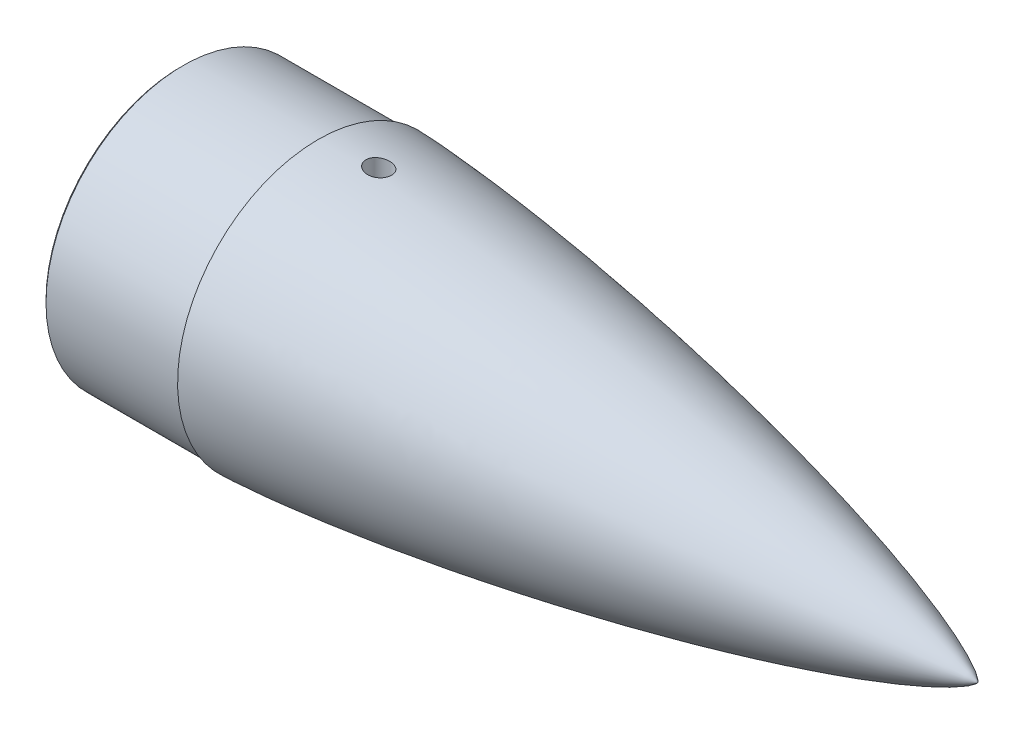
SolidWorks part; units mm, degrees
material "Plain Carbon Steel"
ref_plane "Front Plane" through (0, 0, 0) normal (0, 0, 1) x (1, 0, 0)
ref_plane "Top Plane" through (0, 0, 0) normal (0, 1, 0) x (1, 0, 0)
ref_plane "Right Plane" through (0, 0, 0) normal (1, 0, 0) x (0, 0, -1)
ref_axis "Axis1" through (46.9179, 0, 0) along (-1, 0, 0)
sketch "Sketch10" plane through (0, 0, 0) normal (0, 0, 1) x (1, 0, 0)
  line L1 (-1.0327, 0) -> (486.9547, 0) construction
  line L2 (11.1125, 81.9998) -> (11.1125, 67.4998)
  line L3 (11.1125, 81.9998) -> (-84.6045, 81.9998)
  line L4 (408.9673, 0) -> (368.9673, 0)
  line L5 (-84.6045, 81.9998) -> (-84.6045, 84.9998)
  line L6 (-84.6045, 84.9998) -> (0.3953, 84.9998)
  line L7 (0.3953, 84.9998) -> (0.3953, 86.9998)
  line L8 (11.1125, 67.4998) -> (129.3045, 67.4998)
  spline S0 degree 4 poles (408.9673, 0) (408.9649, 0.0135) (408.958, 0.0399) (408.9365, 0.0905) (408.8922, 0.1741) (408.8263, 0.2756) (408.7217, 0.4158) (408.5611, 0.6051) (408.3056, 0.8724) (407.8697, 1.2753) (407.121, 1.8851) (405.8038, 2.8259) (403.4624, 4.2872) (399.3253, 6.5318) (392.4811, 9.7589) (380.6621, 14.628) (363.6372, 20.7117) (342.2152, 27.4765) (317.4285, 34.4976) (291.8793, 41.1048) (266.2105, 47.229) (240.4455, 52.9334) (214.5989, 58.2554) (188.6809, 63.2176) (165.9462, 67.2533) (146.422, 70.4938) (130.1279, 73.0449) (117.0786, 74.9942) (104.0155, 76.8485) (92.5733, 78.3845) (82.7571, 79.6356) (74.5713, 80.6322) (68.0193, 81.4008) (61.4637, 82.1394) (54.9047, 82.8464) (48.3422, 83.5199) (41.7761, 84.1578) (36.0275, 84.6822) (31.0979, 85.1052) (26.9883, 85.4387) (23.6997, 85.6932) (20.0858, 85.9584) (16.7199, 86.189) (13.6021, 86.387) (10.7327, 86.5546) (8.4366, 86.6787) (6.14, 86.7922) (4.1299, 86.8793) (2.4065, 86.9446) (1.2573, 86.979) (0.6827, 86.9949) (0.3953, 86.9998) knots 0 0 0 0 0 0.00013 0.00026 0.00052 0.0009 0.00128 0.001925 0.002882 0.004418 0.006927 0.011111 0.018279 0.030673 0.051704 0.083102 0.139909 0.202703 0.265496 0.32829 0.391083 0.453877 0.516671 0.579464 0.642258 0.673655 0.705051 0.736448 0.767845 0.799242 0.81494 0.830639 0.846337 0.862036 0.877734 0.893432 0.909131 0.924829 0.932678 0.940527 0.948377 0.956226 0.967169 0.972641 0.978113 0.983585 0.989056 0.994528 0.997264 1 1 1 1 1 construction
  spline S1 degree 4 poles (408.9673, 0) (408.9649, 0.0135) (408.958, 0.0399) (408.9365, 0.0905) (408.8922, 0.1741) (408.8263, 0.2756) (408.7217, 0.4158) (408.5611, 0.6051) (408.3056, 0.8724) (407.8697, 1.2753) (407.121, 1.8851) (405.8038, 2.8259) (403.4624, 4.2872) (399.3253, 6.5318) (392.4811, 9.7589) (380.6621, 14.628) (363.6372, 20.7117) (342.2152, 27.4765) (317.4285, 34.4976) (291.8793, 41.1048) (266.2105, 47.229) (240.4455, 52.9334) (214.5989, 58.2554) (188.6809, 63.2176) (165.9462, 67.2533) (146.422, 70.4938) (130.1279, 73.0449) (117.0786, 74.9942) (104.0155, 76.8485) (92.5733, 78.3845) (82.7571, 79.6356) (74.5713, 80.6322) (68.0193, 81.4008) (61.4637, 82.1394) (54.9047, 82.8464) (48.3422, 83.5199) (41.7761, 84.1578) (36.0275, 84.6822) (31.0979, 85.1052) (26.9883, 85.4387) (23.6997, 85.6932) (20.0858, 85.9584) (16.7199, 86.189) (13.6021, 86.387) (10.7327, 86.5546) (8.4366, 86.6787) (6.14, 86.7922) (4.1299, 86.8793) (2.4065, 86.9446) (1.2573, 86.979) (0.6827, 86.9949) (0.3953, 86.9998) knots 0 0 0 0 0 0.00013 0.00026 0.00052 0.0009 0.00128 0.001925 0.002882 0.004418 0.006927 0.011111 0.018279 0.030673 0.051704 0.083102 0.139909 0.202703 0.265496 0.32829 0.391083 0.453877 0.516671 0.579464 0.642258 0.673655 0.705051 0.736448 0.767845 0.799242 0.81494 0.830639 0.846337 0.862036 0.877734 0.893432 0.909131 0.924829 0.932678 0.940527 0.948377 0.956226 0.967169 0.972641 0.978113 0.983585 0.989056 0.994528 0.997264 1 1 1 1 1
  spline S2 degree 4 poles (368.9673, 0) (368.9653, 0.0123) (368.9594, 0.0365) (368.9406, 0.083) (368.9023, 0.1587) (368.8455, 0.2503) (368.7557, 0.3766) (368.6167, 0.5484) (368.3929, 0.7936) (368.0087, 1.1649) (367.3447, 1.7299) (366.1761, 2.6016) (364.0928, 3.96) (360.426, 6.0407) (354.4022, 9.0183) (344.043, 13.5077) (329.152, 19.1285) (310.4252, 25.3986) (288.7413, 31.9337) (266.3785, 38.1061) (243.9014, 43.8469) (221.332, 49.212) (198.684, 54.2345) (175.9669, 58.9343) (156.0346, 62.7717) (138.9133, 65.8645) (124.6221, 68.3077) (113.1754, 70.1797) (101.7151, 71.9664) (91.6754, 73.4517) (83.0615, 74.6659) (75.8775, 75.6363) (70.1269, 76.3867) (64.3728, 77.1101) (58.6152, 77.8049) (52.854, 78.4695) (47.0892, 79.1019) (42.0417, 79.6247) (37.7129, 80.0488) (34.1039, 80.385) (31.2157, 80.6428) (28.0648, 80.911) (24.6507, 81.1843) (21.4654, 81.4195) (18.5093, 81.6177) (16.0448, 81.767) (14.3191, 81.8612) (12.8395, 81.9336) (11.8527, 81.9739) (11.3593, 81.993) (11.1125, 81.9998) knots 0 0 0 0 0 0.000135 0.00027 0.00054 0.00092 0.001299 0.001947 0.002931 0.004512 0.007081 0.01138 0.018708 0.031424 0.052705 0.084103 0.14091 0.203703 0.266497 0.329291 0.392084 0.454878 0.517672 0.580465 0.643259 0.674656 0.706052 0.737449 0.768846 0.800243 0.815941 0.831639 0.847338 0.863036 0.878735 0.894433 0.910132 0.92583 0.933679 0.941528 0.949378 0.957227 0.96792 0.978613 0.98396 0.989307 0.994653 0.997327 1 1 1 1 1 construction
  spline S3 degree 4 poles (368.9673, 0) (368.9653, 0.0123) (368.9594, 0.0365) (368.9406, 0.083) (368.9023, 0.1587) (368.8455, 0.2503) (368.7557, 0.3766) (368.6167, 0.5484) (368.3929, 0.7936) (368.0087, 1.1649) (367.3447, 1.7299) (366.1761, 2.6016) (364.0928, 3.96) (360.426, 6.0407) (354.4022, 9.0183) (344.043, 13.5077) (329.152, 19.1285) (310.4252, 25.3986) (288.7413, 31.9337) (266.3785, 38.1061) (243.9014, 43.8469) (221.332, 49.212) (198.684, 54.2345) (175.9669, 58.9343) (156.0346, 62.7717) (141.5091, 65.3956) (132.6794, 66.9245) (129.5628, 67.4559) (129.3045, 67.4998) knots 0 0 0 0 0 0.000135 0.00027 0.00054 0.00092 0.001299 0.001947 0.002931 0.004512 0.007081 0.01138 0.018708 0.031424 0.052705 0.084103 0.14091 0.203703 0.266497 0.329291 0.392084 0.454878 0.517672 0.580465 0.643259 0.674656 0.677492 0.677492 0.677492 0.677492 0.677492
  dimension "D1" = 86.9998
  dimension "D2" = 3
  dimension "D3" = 410
  dimension "D4" = 84.9998
  dimension "D5" = 370
  dimension "D6" = 84.9998
  dimension "D7" = 19.5
  dimension "D8" = 118.192
revolve "Revolve1" add sketch "Sketch10" angle 360 about axis through (46.9179, 0, 0) along (-1, 0, 0)
chamfer "Chamfer1" distance 1.5 angle 45 1 edges at (-84.6045, 0, -84.9998)
ref_plane "Plane2" through (11.1125, 0, 0) normal (-1, 0, 0) x (0, 0, 1)
sketch "Sketch12" plane through (11.1125, 0, 0) normal (-1, 0, 0) x (0, 0, 1)
  circle A4 centre (-73.1248, 0) radius 4
  circle A5 centre (-36.5624, 63.328) radius 4
  circle A6 centre (36.5624, 63.328) radius 4
  circle A7 centre (73.1248, 0) radius 4
  circle A8 centre (36.5624, -63.328) radius 4
  circle A9 centre (-36.5624, -63.328) radius 4
  point P2 (0, 0)
  point P17 (-50.2998, -44.6412)
  point P25 (0, 0)
  dimension "D1" = 6
hole_wizard "#96 (0.0063) Diameter Hole1" positions "Sketch17" profile "Sketch18" hole size "#96" standard "ANSI Inch"
sketch "Sketch17" plane through (11.1125, 0, 0) normal (-1, 0, 0) x (0, 0, 1)
  point P0 (-36.5624, 63.328)
sketch "Sketch18" plane through (11.1125, 63.328, -36.5624) normal (0, 1, 0) x (0, 0, 1)
  line L0 (0, 0) -> (0, 9.53)
  line L1 (0, 9.53) -> (3.3782, 9.53)
  line L2 (3.3782, 9.53) -> (3.3782, 0)
  line L5 (3.3782, 0) -> (0, 0)
  line L10 (0, 9.53) -> (-3.3782, 9.53) construction
  line L11 (0, -6.35) -> (0, 107.95) construction
  dimension "Hole Dia." = 6.7564
  dimension "Hole Depth" = 9.53
  dimension "Drill Angle" = 180
pattern_circular "CirPattern1" count 6 over 360 about axis through (0, 0, 0) along (1, 0, 0) of "#96 (0.0063) Diameter Hole1"
ref_plane "Plane3" through (0, 60, 0) normal (0, 1, 0) x (1, 0, 0)
sketch "Sketch20" plane through (0, 60, 0) normal (0, 1, 0) x (1, 0, 0)
  line L0 (46.9179, 0) -> (-46.1272, 0) construction
  line L1 (24.7702, 25) -> (64.7702, 25)
  line L2 (24.7702, 25) -> (24.7702, -15)
  line L3 (24.7702, -15) -> (64.7702, -15)
  line L4 (64.7702, 25) -> (64.7702, -15)
  line L5 (24.7702, 25) -> (64.7702, -15) construction
  line L6 (24.7702, -15) -> (64.7702, 25) construction
  point P4 (44.7702, 5)
  dimension "D1" = 40
  dimension "D2" = 15
  dimension "D3" = 40
extrude "Cut-Extrude3" cut sketch "Sketch20" along normal blind 12
sketch "Sketch22" plane through (0, 60, 0) normal (0, 1, 0) x (1, 0, 0)
  circle A0 centre (32, 6) radius 7.5
  dimension "D1" = 15
extrude "Cut-Extrude4" cut sketch "Sketch22" along normal through all
